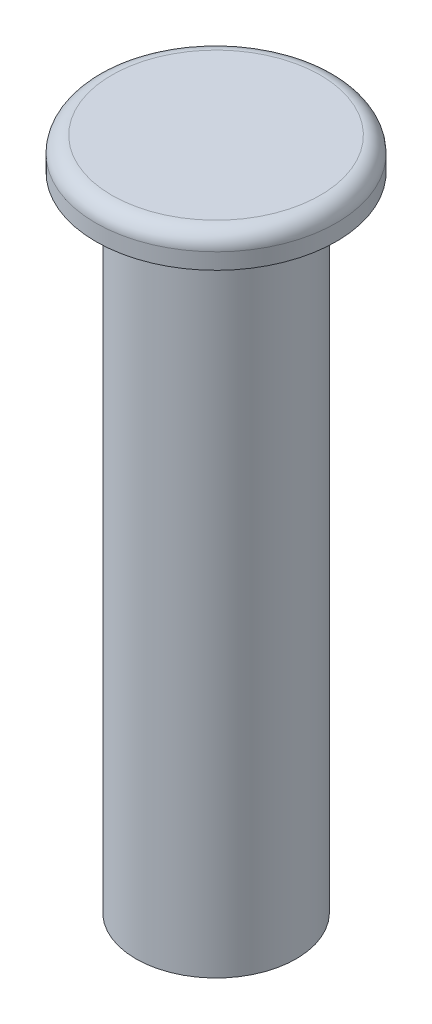
SolidWorks part; units mm, degrees
ref_plane "前视基准面" through (0, 0, 0) normal (0, 0, 1) x (1, 0, 0)
ref_plane "上视基准面" through (0, 0, 0) normal (0, 1, 0) x (1, 0, 0)
ref_plane "右视基准面" through (0, 0, 0) normal (1, 0, 0) x (0, 0, -1)
sketch "草图1" plane through (0, 0, 0) normal (0, 1, 0) x (1, 0, 0)
  circle A0 centre (0, 0) radius 0.5
  dimension "D1" = 1
extrude "凸台-拉伸1" add sketch "草图1" along normal blind 4
sketch "草图2" plane through (0, 4, 0) normal (0, 1, 0) x (1, 0, 0)
  circle A0 centre (0, 0) radius 0.75
  dimension "D1" = 1.5
extrude "凸台-拉伸2" add sketch "草图2" along normal blind 0.2
fillet "圆角1" radius 0.1 1 edges at (0, 4.2, 0.75)
